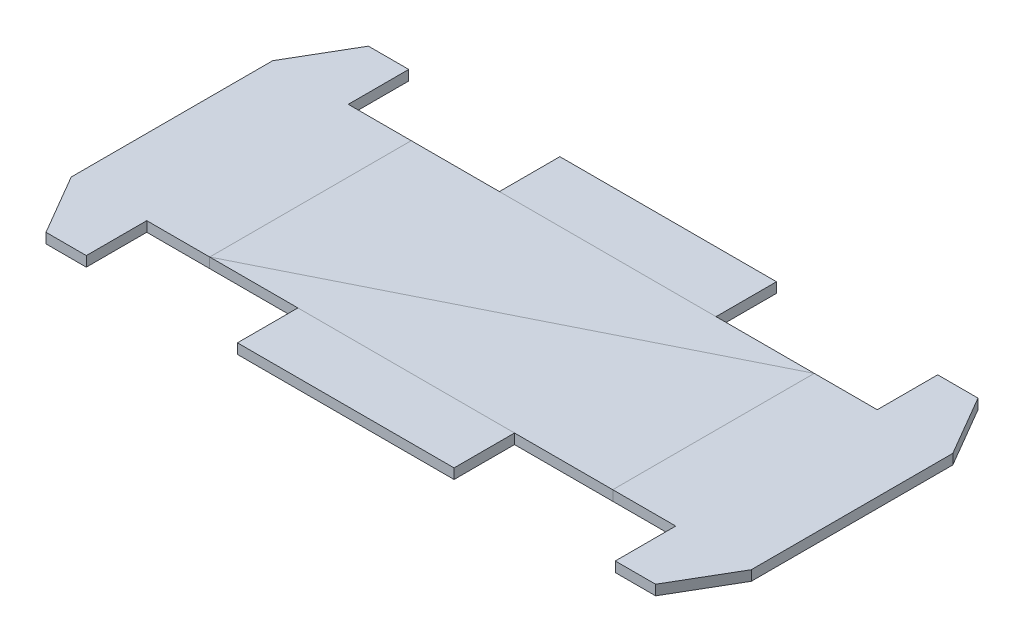
SolidWorks part; units mm, degrees
ref_plane "Front Plane" through (0, 0, 0) normal (0, 0, 1) x (1, 0, 0)
ref_plane "Top Plane" through (0, 0, 0) normal (0, 1, 0) x (1, 0, 0)
ref_plane "Right Plane" through (0, 0, 0) normal (1, 0, 0) x (0, 0, -1)
sketch "Sketch1" plane through (0, 0, 0) normal (0, 1, 0) x (1, 0, 0)
  line L1 (-100, 50) -> (100, 50)
  line L2 (-100, 50) -> (-100, -50)
  line L3 (-100, -50) -> (100, -50)
  line L4 (100, 50) -> (100, -50)
  line L5 (-100, 50) -> (100, -50) construction
  line L6 (-100, -50) -> (100, 50) construction
  point P0 (0, 0)
  dimension "D1" = 200
  dimension "D2" = 100
extrude "Boss-Extrude1" add sketch "Sketch1" along normal blind 5
sketch "Sketch3" plane through (0, 0, 0) normal (0, 0, 1) x (1, 0, 0)
  line L1 (-100, 0) -> (100, 0)
  line L3 (-100, 5) -> (100, 5)
  line L4 (100, 0) -> (100, 5)
  line L6 (-100, 0) -> (-100, 5)
extrude "Boss-Extrude2" add sketch "Sketch3" along normal mid plane 100
sketch "Sketch4" plane through (0, 0, 0) normal (1, 0, 0) x (0, 0, -1)
  line L0 (55, 0) -> (-55, 0) construction
  line L1 (-50, 0) -> (50, 0)
  line L3 (-50, 5) -> (50, 5)
  line L5 (-50, 5) -> (-50, 0) construction
  line L10 (-50, 0) -> (-50, 5)
  line L13 (0, 3) -> (0, 5) construction
  line L17 (50, 0) -> (50, 5)
  dimension "D2" = 5
  dimension "D1" = 100
extrude "Boss-Extrude3" add sketch "Sketch4" along normal mid plane 200 separate body
sketch "Sketch6" plane through (0, 0, 0) normal (0, 1, 0) x (1, 0, 0)
  line L0 (-100, 50) -> (-131.25, 50)
  line L1 (-131.25, 50) -> (-131.25, 80)
  line L2 (-131.25, 80) -> (-151.25, 80)
  line L3 (-168.75, 50) -> (-168.75, -50)
  line L5 (0, 50) -> (0, -50) construction
  line L6 (-131.25, -80) -> (-151.25, -80)
  line L7 (-131.25, -50) -> (-131.25, -80)
  line L8 (-100, -50) -> (-131.25, -50)
  line L9 (-93.75, 31) -> (-93.75, -31) construction
  line L12 (-151.25, 80) -> (-168.75, 50)
  line L13 (-151.25, -80) -> (-168.75, -50)
  line L15 (-56.25, -50) -> (-56.25, -80)
  line L16 (0, -2.75) -> (0, 2.75) construction
  line L19 (100, 50) -> (131.25, 50)
  line L20 (131.25, 50) -> (131.25, 80)
  line L21 (131.25, 80) -> (151.25, 80)
  line L22 (151.25, 80) -> (168.75, 50)
  line L23 (168.75, 50) -> (168.75, -50)
  line L24 (151.25, -80) -> (168.75, -50)
  line L25 (131.25, -80) -> (151.25, -80)
  line L26 (131.25, -50) -> (131.25, -80)
  line L27 (100, -50) -> (131.25, -50)
  line L29 (-56.25, 50) -> (-56.25, 80)
  line L30 (-56.25, 80) -> (51.25, 80)
  line L31 (51.25, 80) -> (51.25, 50)
  line L32 (-100, 0) -> (100, 0) construction
  line L33 (-56.25, -80) -> (51.25, -80)
  line L34 (51.25, -80) -> (51.25, -50)
  line L36 (-100, 50) -> (-100, -50)
  line L37 (-56.25, 50) -> (51.25, 50)
  line L38 (100, 50) -> (100, -50)
  line L39 (51.25, -50) -> (-56.25, -50)
  dimension "D1" = 37.5
  dimension "D4" = 100
  dimension "D2" = 37.5
  dimension "D3" = 20
  dimension "D5" = 30
  dimension "D6" = 30
  dimension "D7" = 75
  dimension "D8" = 80
extrude "Boss-Extrude4" add sketch "Sketch6" along normal blind 5 separate body
sketch "Sketch10" plane through (0, 5, 0) normal (0, 1, 0) x (1, 0, 0)
  line L0 (51.25, 50) -> (131.25, 50) construction
  line L1 (51.25, -50) -> (131.25, -50) construction
  line L2 (91.25, -50) -> (91.25, 50)
  line L3 (-168.75, 0) -> (168.75, 0)
  line L4 (-168.75, 50) -> (-168.75, -50) construction
  line L5 (168.75, -50) -> (168.75, 50) construction
equation "\"car_length\"= 200"
equation "\"car_width\"= 100"
equation "\"platform_width\"= 5"
equation "\"D1@Sketch1\"=\"car_length\""
equation "\"D2@Sketch1\"=\"car_width\""
equation "\"D1@Boss-Extrude1\"=\"platform_width\""
equation "\"D2@Sketch4\"=\"platform_width\""
equation "\"axelholder_width\"= 19"
equation "\"axel_diameter\"= 5.5"
equation "\"axel_holder_diameter\"= 12.5"
equation "\"wheel_size\"=75"
equation "\"D1@Sketch6\"=\"wheel_size\"/2"
equation "\"D1@Boss-Extrude4\"=\"platform_width\""
equation "\"D7@Sketch6\"=\"wheel_size\""
equation "\"D8@Sketch6\"=\"wheel_size\" + 5"
